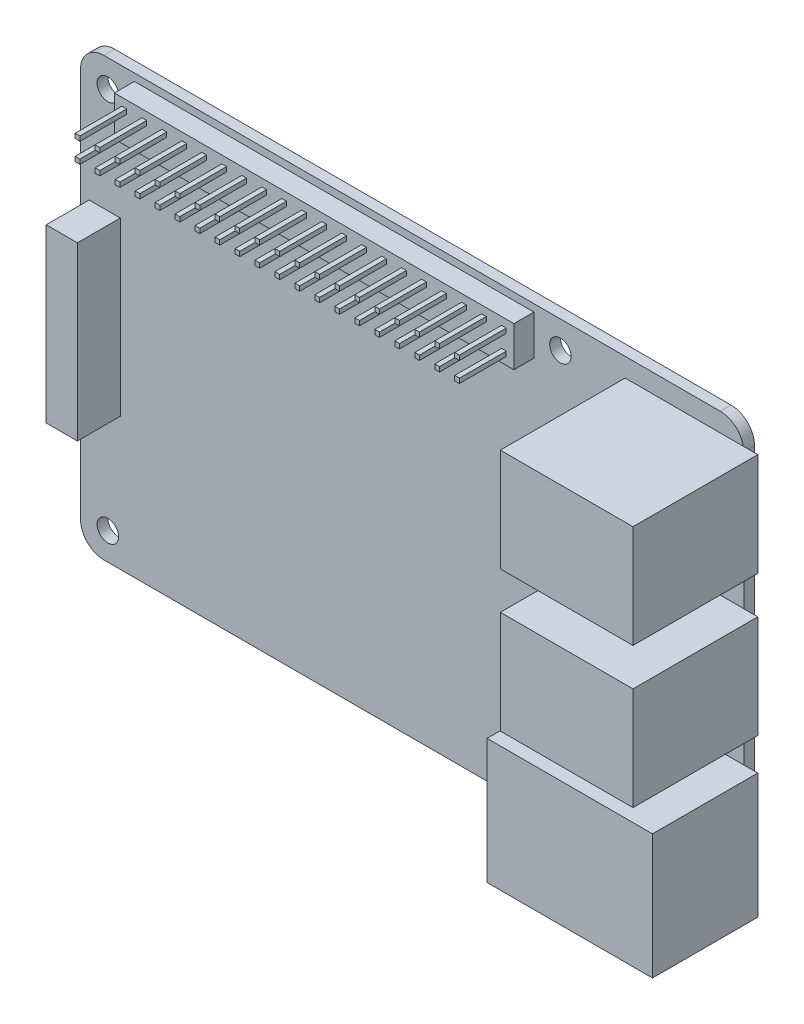
SolidWorks part; units mm, degrees
ref_plane "Plan de face" through (0, 0, 0) normal (0, 0, 1) x (1, 0, 0)
ref_plane "Plan de dessus" through (0, 0, 0) normal (0, 1, 0) x (1, 0, 0)
ref_plane "Plan de droite" through (0, 0, 0) normal (1, 0, 0) x (0, 0, -1)
sketch "Esquisse1" plane through (0, 0, 0) normal (0, 0, 1) x (1, 0, 0)
  line L1 (-39.5, 28) -> (39.5, 28)
  line L2 (-42.5, 25) -> (-42.5, -25)
  line L3 (-39.5, -28) -> (39.5, -28)
  line L4 (42.5, 25) -> (42.5, -25)
  line L5 (-42.5, 28) -> (42.5, -28) construction
  line L6 (-42.5, -28) -> (42.5, 28) construction
  line L7 (19, 24.5) -> (-39, 24.5) construction
  line L8 (19, 24.5) -> (19, -24.5) construction
  line L9 (19, -24.5) -> (-39, -24.5) construction
  line L10 (-39, 24.5) -> (-39, -24.5) construction
  arc A0 (-42.5, -25) -> (-39.5, -28) centre (-39.5, -25) ccw
  arc A1 (39.5, -28) -> (42.5, -25) centre (39.5, -25) ccw
  arc A2 (39.5, 28) -> (42.5, 25) centre (39.5, 25) cw
  arc A3 (-39.5, 28) -> (-42.5, 25) centre (-39.5, 25) ccw
  circle A4 centre (-39, 24.5) radius 1.375
  circle A5 centre (-39, -24.5) radius 1.375
  circle A6 centre (19, -24.5) radius 1.375
  circle A7 centre (19, 24.5) radius 1.375
  point P0 (0, 0)
  dimension "D3" = 3
  dimension "D8" = 2.75
  dimension "D9" = 2.75
  dimension "D10" = 2.75
  dimension "D11" = 2.75
  dimension "D1" = 56
  dimension "D2" = 85
  dimension "D4" = 58
  dimension "D5" = 49
  dimension "D6" = 3.5
  dimension "D7" = 3.5
extrude "Boss.-Extru.1" add sketch "Esquisse1" along normal blind 1.38
sketch "Esquisse2" plane through (0, 0, 1.38) normal (0, 0, 1) x (1, 0, 0)
  line L0 (-39, 24.5) -> (19, 24.5) construction
  line L1 (-35.6, 27.06) -> (15.6, 27.06)
  line L2 (-35.6, 27.06) -> (-35.6, 21.94)
  line L3 (-35.6, 21.94) -> (15.6, 21.94)
  line L4 (15.6, 27.06) -> (15.6, 21.94)
  circle A0 centre (-39, 24.5) radius 1.375 construction
  point P10 (-35.6, 24.5)
  dimension "D3" = 3.4
  dimension "D1" = 5.12
  dimension "D2" = 51.2
extrude "Boss.-Extru.2" add sketch "Esquisse2" along normal blind 2.56
sketch "Esquisse3" plane through (0, 0, 3.94) normal (0, 0, 1) x (1, 0, 0)
  line L0 (15.6, 27.06) -> (-35.6, 27.06) construction
  line L1 (-34.62, 26.08) -> (-34.02, 26.08)
  line L2 (-34.62, 26.08) -> (-34.62, 25.48)
  line L3 (-34.62, 25.48) -> (-34.02, 25.48)
  line L4 (-34.02, 26.08) -> (-34.02, 25.48)
  line L5 (-35.6, 27.06) -> (-35.6, 21.94) construction
  line L6 (-31.46, 26.08) -> (-31.46, 25.48)
  line L7 (-32.06, 26.08) -> (-31.46, 26.08)
  line L8 (-32.06, 26.08) -> (-32.06, 25.48)
  line L9 (-32.06, 25.48) -> (-31.46, 25.48)
  line L10 (-28.9, 26.08) -> (-28.9, 25.48)
  line L11 (-29.5, 26.08) -> (-28.9, 26.08)
  line L12 (-29.5, 26.08) -> (-29.5, 25.48)
  line L13 (-29.5, 25.48) -> (-28.9, 25.48)
  line L14 (-26.34, 26.08) -> (-26.34, 25.48)
  line L15 (-26.94, 26.08) -> (-26.34, 26.08)
  line L16 (-26.94, 26.08) -> (-26.94, 25.48)
  line L17 (-26.94, 25.48) -> (-26.34, 25.48)
  line L18 (-23.78, 26.08) -> (-23.78, 25.48)
  line L19 (-24.38, 26.08) -> (-23.78, 26.08)
  line L20 (-24.38, 26.08) -> (-24.38, 25.48)
  line L21 (-24.38, 25.48) -> (-23.78, 25.48)
  line L22 (-21.22, 26.08) -> (-21.22, 25.48)
  line L23 (-21.82, 26.08) -> (-21.22, 26.08)
  line L24 (-21.82, 26.08) -> (-21.82, 25.48)
  line L25 (-21.82, 25.48) -> (-21.22, 25.48)
  line L26 (-18.66, 26.08) -> (-18.66, 25.48)
  line L27 (-19.26, 26.08) -> (-18.66, 26.08)
  line L28 (-19.26, 26.08) -> (-19.26, 25.48)
  line L29 (-19.26, 25.48) -> (-18.66, 25.48)
  line L30 (-16.1, 26.08) -> (-16.1, 25.48)
  line L31 (-16.7, 26.08) -> (-16.1, 26.08)
  line L32 (-16.7, 26.08) -> (-16.7, 25.48)
  line L33 (-16.7, 25.48) -> (-16.1, 25.48)
  line L34 (-13.54, 26.08) -> (-13.54, 25.48)
  line L35 (-14.14, 26.08) -> (-13.54, 26.08)
  line L36 (-14.14, 26.08) -> (-14.14, 25.48)
  line L37 (-14.14, 25.48) -> (-13.54, 25.48)
  line L38 (-10.98, 26.08) -> (-10.98, 25.48)
  line L39 (-11.58, 26.08) -> (-10.98, 26.08)
  line L40 (-11.58, 26.08) -> (-11.58, 25.48)
  line L41 (-11.58, 25.48) -> (-10.98, 25.48)
  line L42 (-8.42, 26.08) -> (-8.42, 25.48)
  line L43 (-9.02, 26.08) -> (-8.42, 26.08)
  line L44 (-9.02, 26.08) -> (-9.02, 25.48)
  line L45 (-9.02, 25.48) -> (-8.42, 25.48)
  line L46 (-5.86, 26.08) -> (-5.86, 25.48)
  line L47 (-6.46, 26.08) -> (-5.86, 26.08)
  line L48 (-6.46, 26.08) -> (-6.46, 25.48)
  line L49 (-6.46, 25.48) -> (-5.86, 25.48)
  line L50 (-3.3, 26.08) -> (-3.3, 25.48)
  line L51 (-3.9, 26.08) -> (-3.3, 26.08)
  line L52 (-3.9, 26.08) -> (-3.9, 25.48)
  line L53 (-3.9, 25.48) -> (-3.3, 25.48)
  line L54 (-0.74, 26.08) -> (-0.74, 25.48)
  line L55 (-1.34, 26.08) -> (-0.74, 26.08)
  line L56 (-1.34, 26.08) -> (-1.34, 25.48)
  line L57 (-1.34, 25.48) -> (-0.74, 25.48)
  line L58 (1.82, 26.08) -> (1.82, 25.48)
  line L59 (1.22, 26.08) -> (1.82, 26.08)
  line L60 (1.22, 26.08) -> (1.22, 25.48)
  line L61 (1.22, 25.48) -> (1.82, 25.48)
  line L62 (4.38, 26.08) -> (4.38, 25.48)
  line L63 (3.78, 26.08) -> (4.38, 26.08)
  line L64 (3.78, 26.08) -> (3.78, 25.48)
  line L65 (3.78, 25.48) -> (4.38, 25.48)
  line L66 (6.94, 26.08) -> (6.94, 25.48)
  line L67 (6.34, 26.08) -> (6.94, 26.08)
  line L68 (6.34, 26.08) -> (6.34, 25.48)
  line L69 (6.34, 25.48) -> (6.94, 25.48)
  line L70 (9.5, 26.08) -> (9.5, 25.48)
  line L71 (8.9, 26.08) -> (9.5, 26.08)
  line L72 (8.9, 26.08) -> (8.9, 25.48)
  line L73 (8.9, 25.48) -> (9.5, 25.48)
  line L74 (12.06, 26.08) -> (12.06, 25.48)
  line L75 (11.46, 26.08) -> (12.06, 26.08)
  line L76 (11.46, 26.08) -> (11.46, 25.48)
  line L77 (11.46, 25.48) -> (12.06, 25.48)
  line L78 (14.62, 26.08) -> (14.62, 25.48)
  line L79 (14.02, 26.08) -> (14.62, 26.08)
  line L80 (14.02, 26.08) -> (14.02, 25.48)
  line L81 (14.02, 25.48) -> (14.62, 25.48)
  line L82 (-31.46, 23.52) -> (-31.46, 22.92)
  line L83 (-32.06, 23.52) -> (-31.46, 23.52)
  line L84 (-32.06, 23.52) -> (-32.06, 22.92)
  line L85 (-32.06, 22.92) -> (-31.46, 22.92)
  line L86 (-28.9, 23.52) -> (-28.9, 22.92)
  line L87 (-29.5, 23.52) -> (-28.9, 23.52)
  line L88 (-29.5, 23.52) -> (-29.5, 22.92)
  line L89 (-29.5, 22.92) -> (-28.9, 22.92)
  line L90 (-26.34, 23.52) -> (-26.34, 22.92)
  line L91 (-26.94, 23.52) -> (-26.34, 23.52)
  line L92 (-26.94, 23.52) -> (-26.94, 22.92)
  line L93 (-26.94, 22.92) -> (-26.34, 22.92)
  line L94 (-23.78, 23.52) -> (-23.78, 22.92)
  line L95 (-24.38, 23.52) -> (-23.78, 23.52)
  line L96 (-24.38, 23.52) -> (-24.38, 22.92)
  line L97 (-24.38, 22.92) -> (-23.78, 22.92)
  line L98 (-21.22, 23.52) -> (-21.22, 22.92)
  line L99 (-21.82, 23.52) -> (-21.22, 23.52)
  line L100 (-21.82, 23.52) -> (-21.82, 22.92)
  line L101 (-21.82, 22.92) -> (-21.22, 22.92)
  line L102 (-18.66, 23.52) -> (-18.66, 22.92)
  line L103 (-19.26, 23.52) -> (-18.66, 23.52)
  line L104 (-19.26, 23.52) -> (-19.26, 22.92)
  line L105 (-19.26, 22.92) -> (-18.66, 22.92)
  line L106 (-16.1, 23.52) -> (-16.1, 22.92)
  line L107 (-16.7, 23.52) -> (-16.1, 23.52)
  line L108 (-16.7, 23.52) -> (-16.7, 22.92)
  line L109 (-16.7, 22.92) -> (-16.1, 22.92)
  line L110 (-13.54, 23.52) -> (-13.54, 22.92)
  line L111 (-14.14, 23.52) -> (-13.54, 23.52)
  line L112 (-14.14, 23.52) -> (-14.14, 22.92)
  line L113 (-14.14, 22.92) -> (-13.54, 22.92)
  line L114 (-10.98, 23.52) -> (-10.98, 22.92)
  line L115 (-11.58, 23.52) -> (-10.98, 23.52)
  line L116 (-11.58, 23.52) -> (-11.58, 22.92)
  line L117 (-11.58, 22.92) -> (-10.98, 22.92)
  line L118 (-8.42, 23.52) -> (-8.42, 22.92)
  line L119 (-9.02, 23.52) -> (-8.42, 23.52)
  line L120 (-9.02, 23.52) -> (-9.02, 22.92)
  line L121 (-9.02, 22.92) -> (-8.42, 22.92)
  line L122 (-5.86, 23.52) -> (-5.86, 22.92)
  line L123 (-6.46, 23.52) -> (-5.86, 23.52)
  line L124 (-6.46, 23.52) -> (-6.46, 22.92)
  line L125 (-6.46, 22.92) -> (-5.86, 22.92)
  line L126 (-3.3, 23.52) -> (-3.3, 22.92)
  line L127 (-3.9, 23.52) -> (-3.3, 23.52)
  line L128 (-3.9, 23.52) -> (-3.9, 22.92)
  line L129 (-3.9, 22.92) -> (-3.3, 22.92)
  line L130 (-0.74, 23.52) -> (-0.74, 22.92)
  line L131 (-1.34, 23.52) -> (-0.74, 23.52)
  line L132 (-1.34, 23.52) -> (-1.34, 22.92)
  line L133 (-1.34, 22.92) -> (-0.74, 22.92)
  line L134 (1.82, 23.52) -> (1.82, 22.92)
  line L135 (1.22, 23.52) -> (1.82, 23.52)
  line L136 (1.22, 23.52) -> (1.22, 22.92)
  line L137 (1.22, 22.92) -> (1.82, 22.92)
  line L138 (4.38, 23.52) -> (4.38, 22.92)
  line L139 (3.78, 23.52) -> (4.38, 23.52)
  line L140 (3.78, 23.52) -> (3.78, 22.92)
  line L141 (3.78, 22.92) -> (4.38, 22.92)
  line L142 (6.94, 23.52) -> (6.94, 22.92)
  line L143 (6.34, 23.52) -> (6.94, 23.52)
  line L144 (6.34, 23.52) -> (6.34, 22.92)
  line L145 (6.34, 22.92) -> (6.94, 22.92)
  line L146 (9.5, 23.52) -> (9.5, 22.92)
  line L147 (8.9, 23.52) -> (9.5, 23.52)
  line L148 (8.9, 23.52) -> (8.9, 22.92)
  line L149 (8.9, 22.92) -> (9.5, 22.92)
  line L150 (12.06, 23.52) -> (12.06, 22.92)
  line L151 (11.46, 23.52) -> (12.06, 23.52)
  line L152 (11.46, 23.52) -> (11.46, 22.92)
  line L153 (11.46, 22.92) -> (12.06, 22.92)
  line L154 (14.62, 23.52) -> (14.62, 22.92)
  line L155 (14.02, 23.52) -> (14.62, 23.52)
  line L156 (14.02, 23.52) -> (14.02, 22.92)
  line L157 (14.02, 22.92) -> (14.62, 22.92)
  line L158 (-34.02, 23.52) -> (-34.02, 22.92)
  line L159 (-34.62, 23.52) -> (-34.02, 23.52)
  line L160 (-34.62, 23.52) -> (-34.62, 22.92)
  line L161 (-34.62, 22.92) -> (-34.02, 22.92)
  point P4 (-34.62, 25.78)
  point P5 (-34.32, 26.08)
  dimension "D1" = 0.6
  dimension "D2" = 0.6
  dimension "D3" = 1.28
  dimension "D4" = 1.28
  dimension "D5" = 20
  dimension "D6" = 2
extrude "Boss.-Extru.3" add sketch "Esquisse3" along normal blind 6
sketch "Esquisse4" plane through (0, 0, 1.38) normal (0, 0, 1) x (1, 0, 0)
  line L0 (-42.5, 25) -> (-42.5, -25) construction
  line L1 (-41.4, 11) -> (-37.4, 11)
  line L2 (-41.4, 11) -> (-41.4, -11)
  line L3 (-41.4, -11) -> (-37.4, -11)
  line L4 (-37.4, 11) -> (-37.4, -11)
  line L5 (-39.5, -28) -> (39.5, -28) construction
  point P6 (-41.4, 0)
  dimension "D1" = 1.1
  dimension "D2" = 22
  dimension "D3" = 4
  dimension "D4" = 28
extrude "Boss.-Extru.4" add sketch "Esquisse4" along normal blind 5.5
sketch "Esquisse5" plane through (0, 0, 1.38) normal (0, 0, 1) x (1, 0, 0)
  line L0 (42.5, -25) -> (42.5, 25) construction
  line L1 (44.3, 25.59) -> (27.3, 25.59)
  line L2 (44.3, 25.59) -> (44.3, 12.41)
  line L3 (44.3, 12.41) -> (27.3, 12.41)
  line L4 (27.3, 25.59) -> (27.3, 12.41)
  line L5 (44.3, 7.59) -> (27.3, 7.59)
  line L6 (44.3, 7.59) -> (44.3, -5.59)
  line L7 (44.3, -5.59) -> (27.3, -5.59)
  line L8 (27.3, 7.59) -> (27.3, -5.59)
  line L9 (-39.5, -28) -> (39.5, -28) construction
  point P10 (44.3, 19)
  point P11 (44.3, 1)
  dimension "D1" = 1.8
  dimension "D2" = 1.8
  dimension "D3" = 13.18
  dimension "D4" = 13.18
  dimension "D5" = 47
  dimension "D6" = 29
  dimension "D7" = 17
  dimension "D8" = 17
extrude "Boss.-Extru.5" add sketch "Esquisse5" along normal blind 16
sketch "Esquisse6" plane through (0, 0, 1.38) normal (0, 0, 1) x (1, 0, 0)
  line L0 (44.3, -5.59) -> (44.3, 7.59) construction
  line L1 (44.3, -9.75) -> (23.1, -9.75)
  line L2 (44.3, -9.75) -> (44.3, -25.75)
  line L3 (44.3, -25.75) -> (23.1, -25.75)
  line L4 (23.1, -9.75) -> (23.1, -25.75)
  line L5 (-39.5, -28) -> (39.5, -28) construction
  point P6 (44.3, -17.75)
  dimension "D1" = 16
  dimension "D2" = 21.2
  dimension "D3" = 10.25
extrude "Boss.-Extru.6" add sketch "Esquisse6" along normal blind 13.5
